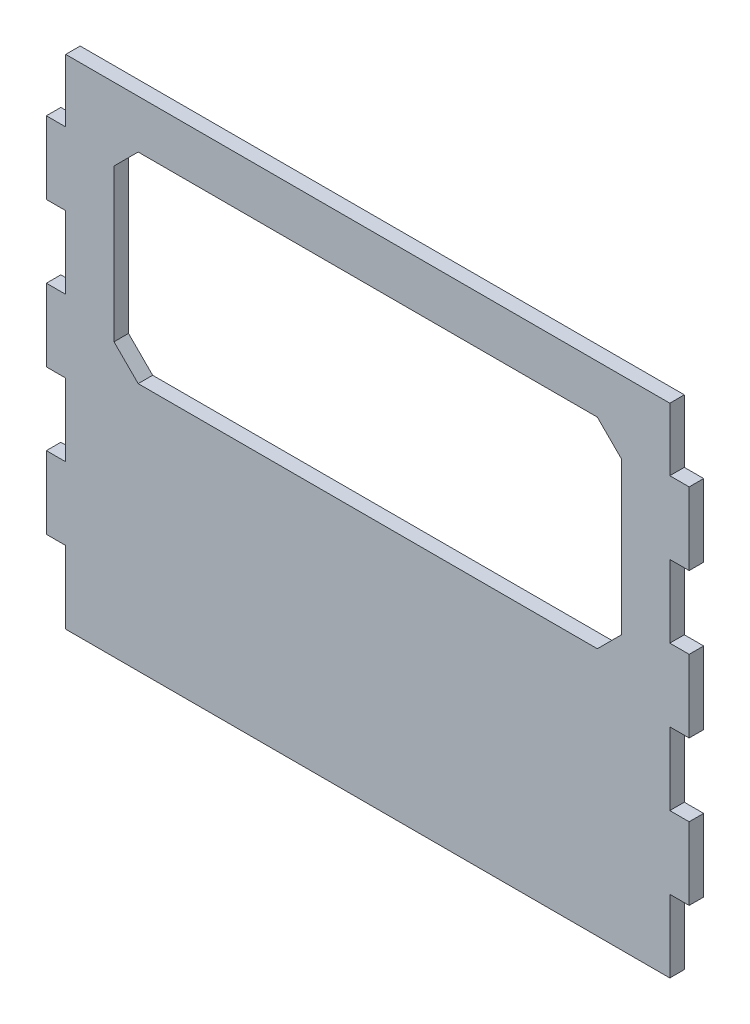
SolidWorks part; units mm, degrees
ref_plane "Front Plane" through (0, 0, 0) normal (0, 0, 1) x (1, 0, 0)
ref_plane "Top Plane" through (0, 0, 0) normal (0, 1, 0) x (1, 0, 0)
ref_plane "Right Plane" through (0, 0, 0) normal (1, 0, 0) x (0, 0, -1)
sketch "Sketch1" plane through (0, 0, 0) normal (0, 0, 1) x (1, 0, 0)
  line L1 (0, 0) -> (-125, 0)
  line L2 (0, 0) -> (0, 103)
  line L3 (0, 103) -> (-125, 103)
  line L4 (-125, 0) -> (-125, 103)
  line L12 (-15, 93) -> (-110, 93)
  line L13 (-115, 56.5) -> (-115, 88)
  line L15 (-10, 56.5) -> (-10, 88)
  line L16 (-110, 51.5) -> (-15, 51.5)
  line L17 (-115, 10) -> (-115, 93) construction
  line L18 (-10, 10) -> (-10, 93) construction
  line L19 (-10, 10) -> (-115, 10) construction
  line L20 (-10, 93) -> (-115, 93) construction
  line L21 (-110, 93) -> (-115, 88)
  line L22 (-10, 88) -> (-15, 93)
  line L23 (-15, 51.5) -> (-10, 56.5)
  line L24 (-115, 56.5) -> (-110, 51.5)
  point P9 (-115, 51.5)
  point P10 (-10, 51.5)
  dimension "D1" = 125
  dimension "D2" = 103
  dimension "D3" = 10
extrude "Boss-Extrude1" add sketch "Sketch1" along normal blind 3
sketch "Sketch2" plane through (0, 0, 3) normal (0, 0, 1) x (1, 0, 0)
  line L4 (0, 90) -> (0, 75)
  line L5 (-62.5, 103) -> (-62.5, 0) construction
  line L6 (4, 75) -> (4, 90)
  line L7 (0, 15) -> (4, 15)
  line L8 (0, 103) -> (-125, 103) construction
  line L9 (-125, 0) -> (0, 0) construction
  line L11 (-129, 15) -> (-129, 30)
  line L16 (0, 30) -> (4, 30)
  line L17 (0, 45) -> (4, 45)
  line L18 (0, 60) -> (4, 60)
  line L19 (0, 75) -> (4, 75)
  line L20 (0, 90) -> (4, 90)
  line L21 (0, 60) -> (0, 45)
  line L22 (4, 45) -> (4, 60)
  line L23 (0, 30) -> (0, 15)
  line L24 (4, 15) -> (4, 30)
  line L25 (-125, 30) -> (-125, 15)
  line L26 (-129, 45) -> (-129, 60)
  line L27 (-125, 60) -> (-125, 45)
  line L28 (-125, 90) -> (-129, 90)
  line L29 (-125, 75) -> (-129, 75)
  line L30 (-125, 60) -> (-129, 60)
  line L31 (-125, 45) -> (-129, 45)
  line L32 (-125, 30) -> (-129, 30)
  line L33 (-125, 15) -> (-129, 15)
  line L34 (-129, 75) -> (-129, 90)
  line L35 (-125, 90) -> (-125, 75)
  dimension "D3" = 15
  dimension "D4" = 15
  dimension "D5" = 15
  dimension "D6" = 15
  dimension "D7" = 15
extrude "Boss-Extrude2" add sketch "Sketch2" against normal blind 3
